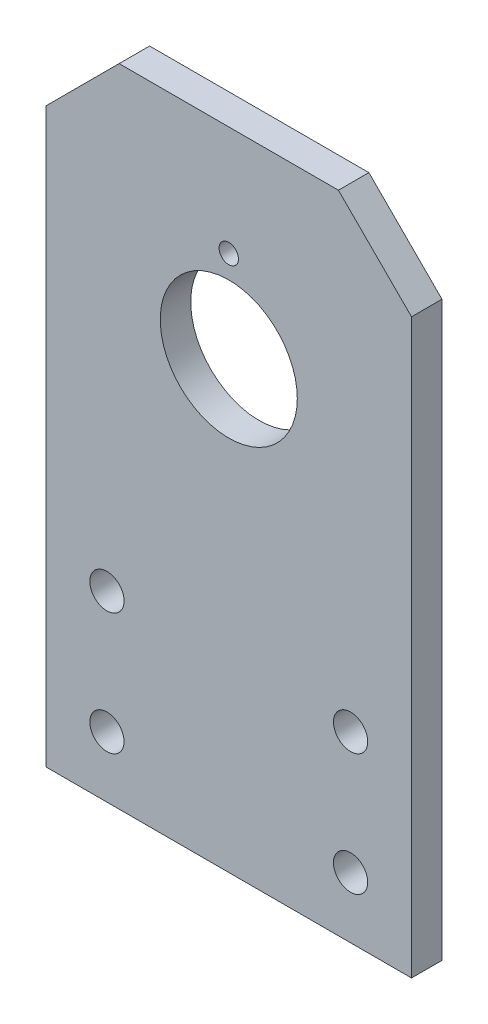
SolidWorks part; units mm, degrees
material "1060 Alloy"
ref_plane "Front Plane" through (0, 0, 0) normal (0, 0, 1) x (1, 0, 0)
ref_plane "Top Plane" through (0, 0, 0) normal (0, 1, 0) x (1, 0, 0)
ref_plane "Right Plane" through (0, 0, 0) normal (1, 0, 0) x (0, 0, -1)
sketch "Sketch1" plane through (0, 0, 0) normal (0, 0, 1) x (1, 0, 0)
  line L1 (0, 0) -> (76.2, 0)
  line L2 (0, 0) -> (0, -134.62)
  line L3 (0, -134.62) -> (76.2, -134.62)
  line L4 (76.2, 0) -> (76.2, -134.62)
  dimension "D1" = 134.62
  dimension "D2" = 76.2
extrude "Boss-Extrude1" add sketch "Sketch1" along normal blind 6.35
sketch "Sketch2" plane through (0, 0, 6.35) normal (0, 0, 1) x (1, 0, 0)
  line L0 (76.2, -134.62) -> (76.2, 0) construction
  line L1 (76.2, 0) -> (0, 0) construction
  circle A0 centre (38.1, -41.91) radius 14.2875
  point P6 (38.1, 0)
  dimension "D3" = 28.575
  dimension "D1" = 38.1
  dimension "D2" = 41.91
extrude "Cut-Extrude1" cut sketch "Sketch2" against normal through all
sketch "Sketch3" plane through (0, 0, 6.35) normal (0, 0, 1) x (1, 0, 0)
  line L0 (0, -134.62) -> (76.2, -134.62) construction
  line L1 (0, 0) -> (0, -134.62) construction
  line L2 (76.2, -134.62) -> (76.2, 0) construction
  circle A0 centre (12.7, -121.92) radius 3.5719
  circle A1 centre (63.5, -121.92) radius 3.5719
  circle A2 centre (12.7, -96.52) radius 3.5719
  circle A3 centre (63.5, -96.52) radius 3.5719
  dimension "D1" = 7.1437
  dimension "D2" = 7.1437
  dimension "D3" = 7.1437
  dimension "D4" = 7.1437
  dimension "D5" = 12.7
  dimension "D6" = 12.7
  dimension "D7" = 12.7
  dimension "D8" = 12.7
  dimension "D9" = 12.7
  dimension "D10" = 12.7
  dimension "D11" = 25.4
  dimension "D12" = 25.4
extrude "Cut-Extrude2" cut sketch "Sketch3" against normal through all
chamfer "Chamfer1" distance 15.24 angle 45 2 edges at (0, 0, 3.175) (76.2, 0, 3.175)
hole_wizard "#10-32 Tapped Hole1" positions "Sketch4" profile "Sketch5" tap size "#10-32" standard "ANSI Inch" end condition through all
sketch "Sketch4" plane through (0, 0, 6.35) normal (0, 0, 1) x (1, 0, 0)
  line L1 (38.1, 0) -> (38.1, -63.4636) construction
  line L2 (60.96, 0) -> (15.24, 0) construction
  circle A0 centre (38.1, -41.91) radius 14.2875 construction
  point P0 (38.1, -22.86)
  dimension "D1" = 19.05
sketch "Sketch5" plane through (38.1, -22.86, 6.35) normal (1, 0, 0) x (0, -1, 0)
  line L0 (0, 0) -> (0, 6.35)
  line L1 (0, 6.35) -> (2.0193, 6.35)
  line L2 (2.0193, 6.35) -> (2.0193, 0)
  line L5 (2.0193, 0) -> (0, 0)
  line L11 (0, -6.35) -> (0, 107.95) construction
  dimension "Thru Tap Drill Dia." = 4.0386
  dimension "Thru Tap Drill Depth" = 6.35
cosmetic thread "Hole Thread1" parameters "D2"=4.826
